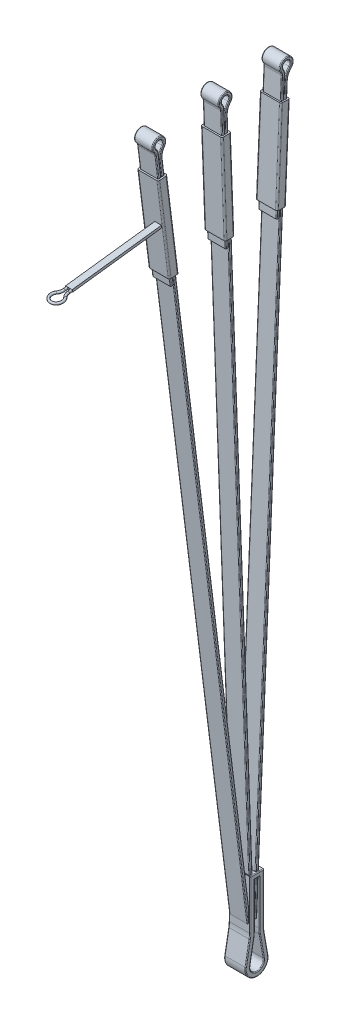
SolidWorks part; units mm, degrees
ref_plane "Front Plane" through (0, 0, 0) normal (0, 0, 1) x (1, 0, 0)
ref_plane "Top Plane" through (0, 0, 0) normal (0, 1, 0) x (1, 0, 0)
ref_plane "Right Plane" through (0, 0, 0) normal (1, 0, 0) x (0, 0, -1)
sketch "Sketch1" plane through (0, 0, 0) normal (1, 0, 0) x (0, 0, -1)
  line L0 (4.3747, 25) -> (-9.6391, 25)
  line L1 (-52.4533, 141.357) -> (-152.4533, 141.357)
  line L2 (-52.4533, 141.357) -> (-52.4533, 41.357)
  line L3 (-52.4533, 41.357) -> (-152.4533, 41.357)
  line L4 (-152.4533, 141.357) -> (-152.4533, 41.357)
  line L5 (297.6273, 0) -> (-297.6273, 0) construction
  circle A0 centre (0, 0) radius 3
  arc A1 (157.835, 474.4345) -> (-383.3056, 321.0558) centre (0, 0) ccw
  circle A2 centre (20.511, 499.5791) radius 2.5
  circle A3 centre (-19.5807, 499.6164) radius 2.5
  circle A4 centre (-62.9852, 496.017) radius 2.5
  circle A5 centre (-20.8326, 378.6697) radius 2.5
  circle A6 centre (-19.5807, 358.7365) radius 2.5
  circle A7 centre (1.5224, 319.8015) radius 2.5
  circle A8 centre (5.7672, 300.2906) radius 2.5
  circle A9 centre (22.2613, 244.8544) radius 2.5
  circle A10 centre (15.2521, 89.8544) radius 2.5
  circle A11 centre (-149.2518, 426.6446) radius 2.5
  dimension "D1" = 6
  dimension "D4" = 500
  dimension "D5" = 5
  dimension "D6" = 155
  dimension "D2" = 100
  dimension "D3" = 100
  dimension "D7" = 1.5224
  dimension "D8" = 5.7672
  dimension "D9" = 15.2521
  dimension "D10" = 20.511
  dimension "D11" = 22.2613
  dimension "D12" = 157.835
  dimension "D13" = 19.5807
  dimension "D14" = 20.8326
  dimension "D15" = 62.9852
  dimension "D16" = 383.3056
  dimension "D17" = 25
sketch "Sketch3" plane through (0, 0, 0) normal (1, 0, 0) x (0, 0, -1)
  line L0 (20.1194, 490.5184) -> (0, 25)
  line L1 (4.3747, 25) -> (-9.6391, 25) construction
  line L2 (0, 278.3435) -> (0, -278.3435) construction
  line L3 (18.3186, 495.1697) -> (14.861, 415.1697)
  arc A0 (22.9997, 497.1181) -> (17.623, 497.602) centre (20.511, 499.5791) ccw
  arc A1 (20.1194, 490.5184) -> (22.9997, 497.1181) centre (30.1101, 490.0866) cw
  arc A2 (17.623, 497.602) -> (18.3186, 495.1697) centre (14.3223, 495.3424) cw
  dimension "D1" = 7
  dimension "D2" = 10
  dimension "D4" = 4
  dimension "D3" = 2
  dimension "D5" = 80
sketch "Sketch7" plane through (0, 0, 0) normal (1, 0, 0) x (0, 0, -1)
  line L0 (3, 50) -> (3, 19.2886)
  line L1 (0, 277.814) -> (0, -277.814) construction
  line L2 (3.3038, 15.8156) -> (5.9088, 1.0419)
  line L3 (297.6273, 0) -> (-297.6273, 0) construction
  line L4 (0, 0) -> (0, 3) construction
  line L5 (-3.3038, 15.8156) -> (-5.9088, 1.0419)
  line L6 (-3, 50) -> (-3, 19.2886)
  line L7 (3, 50) -> (-3, 50)
  arc A0 (-5.9088, 1.0419) -> (5.9088, 1.0419) centre (0, 0) ccw
  circle A1 centre (0, 0) radius 3 construction
  arc A2 (-3.3038, 15.8156) -> (-3, 19.2886) centre (-23, 19.2886) ccw
  arc A3 (3, 19.2886) -> (3.3038, 15.8156) centre (23, 19.2886) ccw
  point P17 (-3, 17.5388)
  point P20 (3, 17.5388)
  dimension "D1" = 12
  dimension "D5" = 20
  dimension "D2" = 3
  dimension "D3" = 10
  dimension "D4" = 50
ref_plane "Plane2" through (0, 50, -3) normal (0, -1, 0) x (1, 0, 0)
sketch "Sketch8" plane through (0, 50, -3) normal (0, -1, 0) x (1, 0, 0)
  line L0 (0, -154.835) -> (0, 386.3056) construction
  line L1 (-6.5, 1.5) -> (6.5, 1.5)
  line L2 (-7, 1) -> (-7, -1)
  line L3 (-6.5, -1.5) -> (6.5, -1.5)
  line L4 (7, 1) -> (7, -1)
  arc A0 (6.5, -1.5) -> (7, -1) centre (6.5, -1) ccw
  arc A1 (6.5, 1.5) -> (7, 1) centre (6.5, 1) cw
  arc A2 (-6.5, 1.5) -> (-7, 1) centre (-6.5, 1) ccw
  arc A3 (-7, -1) -> (-6.5, -1.5) centre (-6.5, -1) ccw
  point P9 (7, -1.5)
  point P12 (7, 1.5)
  point P17 (-7, -1.5)
  dimension "D5" = 0.5
  dimension "D1" = 14
  dimension "D2" = 3
  dimension "D3" = 7
  dimension "D4" = 1.5
sweep "Sweep2" add profiles "Sketch8" path "Sketch7"
ref_plane "Plane1" through (0, 415.1697, -14.861) normal (0, -0.9991, 0.0432) x (1, 0, 0)
sketch "Sketch5" plane through (0, 415.1697, -14.861) normal (0, -0.9991, 0.0432) x (1, 0, 0)
  line L0 (0, -4.5) -> (0, 0.5) construction
  line L1 (-5.5, 1) -> (5.5, 1)
  line L2 (-6, 0.5) -> (-6, -0.5)
  line L3 (-5.5, -1) -> (5.5, -1)
  line L4 (6, 0.5) -> (6, -0.5)
  arc A0 (-6, -0.5) -> (-5.5, -1) centre (-5.5, -0.5) ccw
  arc A1 (5.5, -1) -> (6, -0.5) centre (5.5, -0.5) ccw
  arc A2 (5.5, 1) -> (6, 0.5) centre (5.5, 0.5) cw
  arc A3 (-5.5, 1) -> (-6, 0.5) centre (-5.5, 0.5) ccw
  point P0 (0, 0)
  point P12 (6, -1)
  point P15 (6, 1)
  point P18 (-6, 1)
  dimension "D5" = 0.5
  dimension "D1" = 12
  dimension "D2" = 2
  dimension "D3" = 1
  dimension "D4" = 6
sweep "Sweep1" add profiles "Sketch5" path "Sketch3"
pattern_circular "CirPattern1" count 2 over 355.4 about axis through (0, 0, 0) along (1, 0, 0) of "Sweep1"
pattern_circular "CirPattern2" count 2 over 350.4 about axis through (0, 0, 0) along (1, 0, 0) of "Sweep1"
sketch "Sketch9" plane through (0, 0.0034, 0.0794) normal (0, -0.0432, -0.9991) x (-1, 0, 0)
  line L0 (-5.5, 490.9297) -> (5.5, 490.9297) construction
  line L1 (-7, 480.9297) -> (7, 480.9297)
  line L2 (-7, 480.9297) -> (-7, 420.9297)
  line L3 (-7, 420.9297) -> (7, 420.9297)
  line L4 (7, 480.9297) -> (7, 420.9297)
  line L5 (0, 281.3882) -> (0, -281.3882) construction
  dimension "D1" = 10
  dimension "D2" = 60
  dimension "D3" = 14
  dimension "D4" = 7
extrude "Boss-Extrude2" add sketch "Sketch9" along normal blind 1 and the other way blind 5 separate body
fillet "Fillet1" radius 1 4 edges at (7, 450.7284, -14.396) (7, 450.4693, -20.3904) (-7, 450.7284, -14.396) (-7, 450.4693, -20.3904)
pattern_circular "CirPattern3" count 2 over 355.4 about axis through (0, 0, 0) along (1, 0, 0) of bodies 105
pattern_circular "CirPattern4" count 2 over 350.4 about axis through (0, 0, 0) along (1, 0, 0) of bodies 105
sketch "Sketch10" plane through (0, -0.506, 4.048) normal (0, -0.124, 0.9923) x (1, 0, 0)
  line L1 (1.2549, 453.4358) -> (5.6069, 453.4358)
  line L2 (1.2549, 453.4358) -> (1.2549, 451.8261)
  line L3 (1.2549, 451.8261) -> (5.6069, 451.8261)
  line L4 (5.6069, 453.4358) -> (5.6069, 451.8261)
extrude "Boss-Extrude4" add sketch "Sketch10" along normal blind 60 separate body
sketch "Sketch11" plane through (0, 449.934, 56.2436) normal (0, 0.9923, 0.124) x (1, 0, 0)
  line L0 (1.9924, -64.0795) -> (1.9924, -65.9555)
  line L1 (5.6069, -64.0795) -> (1.2549, -64.0795) construction
  line L2 (4.9924, -64.0795) -> (4.9924, -65.9171)
  arc A0 (0.6138, -69.4031) -> (6.3915, -69.386) centre (3.5108, -72.1612) ccw
  arc A1 (4.9924, -65.9171) -> (6.3915, -69.386) centre (9.9924, -65.9171) ccw
  arc A2 (1.9924, -65.9555) -> (0.6138, -69.4031) centre (-3.0076, -65.9555) cw
  point P9 (4.9924, -68.4457)
  dimension "D1" = 8
  dimension "D4" = 5
  dimension "D2" = 3
  dimension "D3" = 4.3662
sketch "Sketch12" plane through (0, -7.9483, 63.5846) normal (0, -0.124, 0.9923) x (1, 0, 0)
  circle A0 centre (2.0568, 452.6271) radius 0.7614
sweep "Sweep3" add profiles "Sketch12" path "Sketch11"
